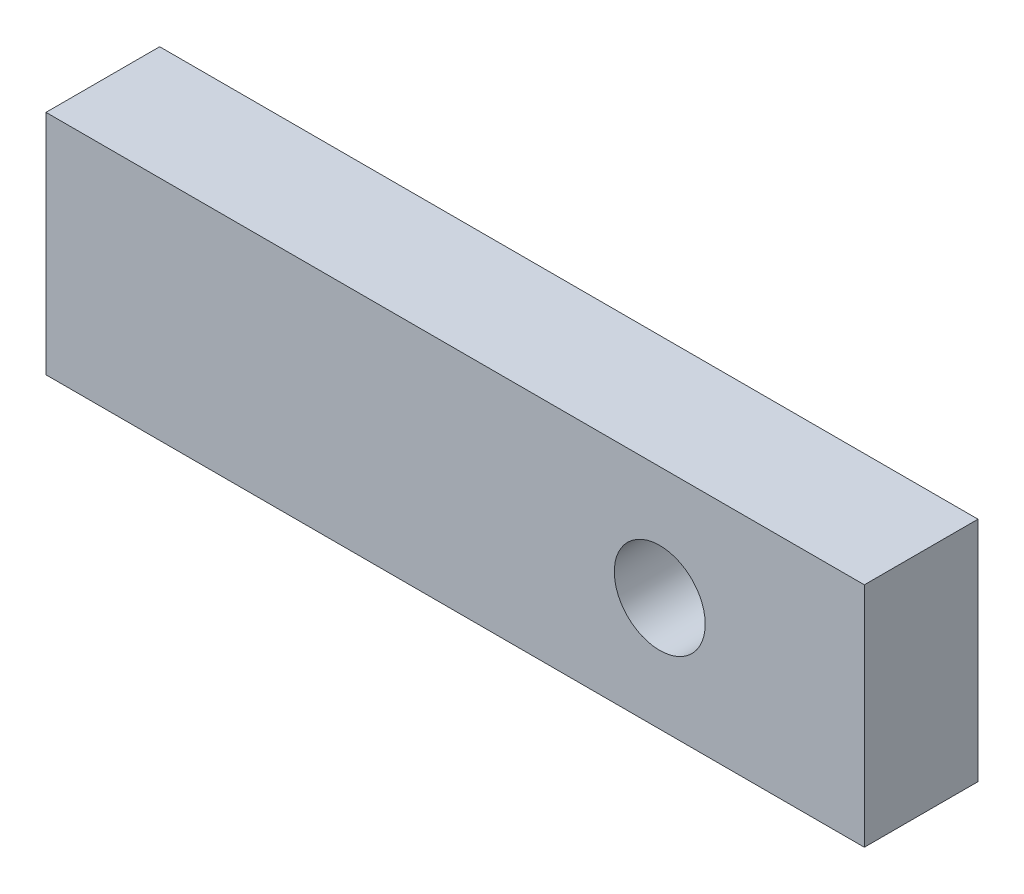
SolidWorks part; units mm, degrees
ref_plane "Front Plane" through (0, 0, 0) normal (0, 0, 1) x (1, 0, 0)
ref_plane "Top Plane" through (0, 0, 0) normal (0, 1, 0) x (1, 0, 0)
ref_plane "Right Plane" through (0, 0, 0) normal (1, 0, 0) x (0, 0, -1)
sketch "Sketch1" plane through (0, 0, 0) normal (0, 1, 0) x (1, 0, 0)
  line L0 (0, 1.25) -> (0, 0) construction
  line L1 (-9, 0) -> (9, 0)
  line L2 (-9, 0) -> (-9, 2.5)
  line L3 (-9, 2.5) -> (9, 2.5)
  line L4 (9, 0) -> (9, 2.5)
  line L5 (-9, 0) -> (9, 2.5) construction
  line L6 (-9, 2.5) -> (9, 0) construction
  circle A0 centre (0, 0) radius 12.5 construction
  point P3 (0, 1.25)
  dimension "D1" = 25
  dimension "D2" = 1.25
  dimension "D3" = 18
  dimension "D4" = 2.5
extrude "Boss-Extrude1" add sketch "Sketch1" along normal blind 5
sketch "Sketch2" plane through (0, 0, 0) normal (0, 0, 1) x (1, 0, 0)
  circle A0 centre (4.5, 2.5) radius 1
  point P5 (0, 0)
  point P6 (-1.9009, 3.153)
  dimension "D1" = 2
  dimension "D2" = 4.5
  dimension "D3" = 2.5
extrude "Cut-Extrude1" cut sketch "Sketch2" against normal up to surface (2.5 mm away) up to face at (0, 2.5, -2.5)
